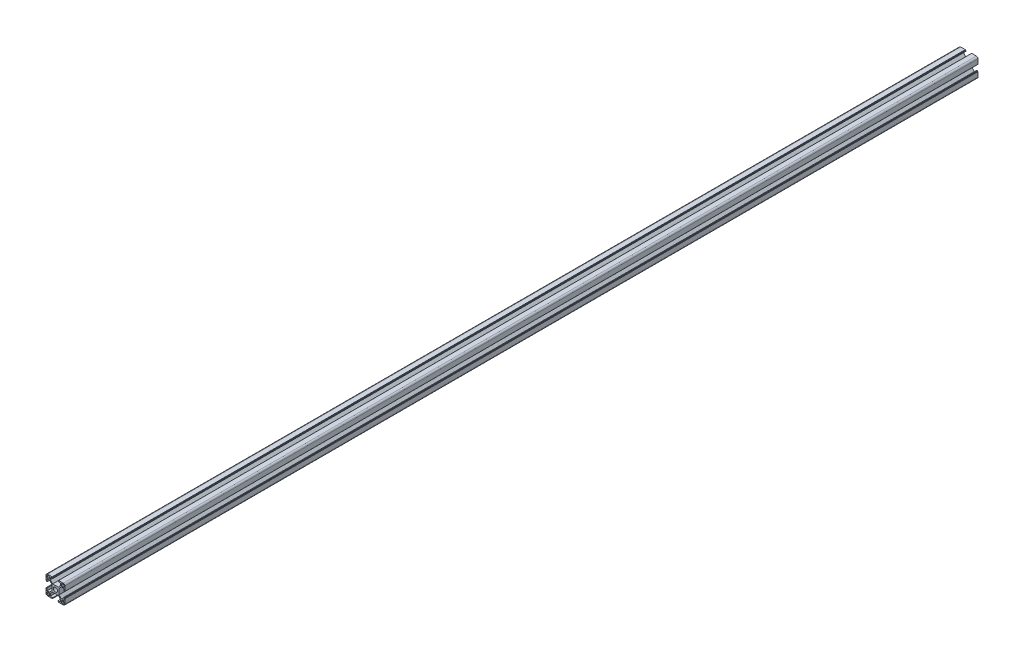
SolidWorks part; units mm, degrees
material "6061-T6 (SS)"
ref_plane "前视基准面" through (0, 0, 0) normal (0, 0, 1) x (1, 0, 0)
ref_plane "上视基准面" through (0, 0, 0) normal (0, 1, 0) x (1, 0, 0)
ref_plane "右视基准面" through (0, 0, 0) normal (1, 0, 0) x (0, 0, -1)
sketch "Sketch1" plane through (0, 0, 0) normal (0, 0, 1) x (1, 0, 0)
  line L0 (-5.1, 15) -> (-5.1, 14.2)
  line L1 (-12.5, -15) -> (12.5, -15)
  line L2 (-15, -12.5) -> (-15, 12.5)
  line L3 (-12.5, 15) -> (12.5, 15)
  line L4 (15, -12.5) -> (15, 12.5)
  line L5 (-15, -15) -> (15, 15) construction
  line L6 (-15, 15) -> (15, -15) construction
  line L7 (-5.1, 14.2) -> (-4.1, 14.2)
  line L8 (-4.1, 14.2) -> (-4.1, 13.2)
  line L9 (-4.1, 13.2) -> (-8.25, 13.2)
  line L10 (-8.25, 13.2) -> (-8.25, 9.5228)
  line L11 (-8.25, 9.5228) -> (-4.4272, 5.7)
  line L12 (-4.4272, 5.7) -> (4.4272, 5.7)
  line L13 (-5.1, 15) -> (5.1, 15)
  line L14 (0, 15) -> (0, 5.7) construction
  line L15 (8.25, 9.5228) -> (4.4272, 5.7)
  line L16 (8.25, 13.2) -> (8.25, 9.5228)
  line L17 (4.1, 13.2) -> (8.25, 13.2)
  line L18 (4.1, 14.2) -> (4.1, 13.2)
  line L19 (5.1, 14.2) -> (4.1, 14.2)
  line L20 (5.1, 15) -> (5.1, 14.2)
  line L21 (15, 5.1) -> (14.2, 5.1)
  line L22 (14.2, 5.1) -> (14.2, 4.1)
  line L23 (14.2, 4.1) -> (13.2, 4.1)
  line L24 (13.2, 4.1) -> (13.2, 8.25)
  line L25 (13.2, 8.25) -> (9.5228, 8.25)
  line L26 (9.5228, 8.25) -> (5.7, 4.4272)
  line L27 (5.7, 4.4272) -> (5.7, -4.4272)
  line L28 (15, 5.1) -> (15, -5.1)
  line L29 (9.5228, -8.25) -> (5.7, -4.4272)
  line L30 (13.2, -8.25) -> (9.5228, -8.25)
  line L31 (13.2, -4.1) -> (13.2, -8.25)
  line L32 (14.2, -4.1) -> (13.2, -4.1)
  line L33 (14.2, -5.1) -> (14.2, -4.1)
  line L34 (15, -5.1) -> (14.2, -5.1)
  line L35 (15, 0) -> (5.7, 0) construction
  line L36 (5.1, -15) -> (5.1, -14.2)
  line L37 (5.1, -14.2) -> (4.1, -14.2)
  line L38 (4.1, -14.2) -> (4.1, -13.2)
  line L39 (4.1, -13.2) -> (8.25, -13.2)
  line L40 (8.25, -13.2) -> (8.25, -9.5228)
  line L41 (8.25, -9.5228) -> (4.4272, -5.7)
  line L42 (4.4272, -5.7) -> (-4.4272, -5.7)
  line L43 (5.1, -15) -> (-5.1, -15)
  line L44 (-8.25, -9.5228) -> (-4.4272, -5.7)
  line L45 (-8.25, -13.2) -> (-8.25, -9.5228)
  line L46 (-4.1, -13.2) -> (-8.25, -13.2)
  line L47 (-4.1, -14.2) -> (-4.1, -13.2)
  line L48 (-5.1, -14.2) -> (-4.1, -14.2)
  line L49 (-5.1, -15) -> (-5.1, -14.2)
  line L50 (0, -15) -> (0, -5.7) construction
  line L51 (-15, -5.1) -> (-14.2, -5.1)
  line L52 (-14.2, -5.1) -> (-14.2, -4.1)
  line L53 (-14.2, -4.1) -> (-13.2, -4.1)
  line L54 (-13.2, -4.1) -> (-13.2, -8.25)
  line L55 (-13.2, -8.25) -> (-9.5228, -8.25)
  line L56 (-9.5228, -8.25) -> (-5.7, -4.4272)
  line L57 (-5.7, -4.4272) -> (-5.7, 4.4272)
  line L58 (-15, -5.1) -> (-15, 5.1)
  line L59 (-9.5228, 8.25) -> (-5.7, 4.4272)
  line L60 (-13.2, 8.25) -> (-9.5228, 8.25)
  line L61 (-13.2, 4.1) -> (-13.2, 8.25)
  line L62 (-14.2, 4.1) -> (-13.2, 4.1)
  line L63 (-14.2, 5.1) -> (-14.2, 4.1)
  line L64 (-15, 5.1) -> (-14.2, 5.1)
  line L65 (-15, 0) -> (-5.7, 0) construction
  line L66 (0, 0) -> (0, 5.7) construction
  circle A0 centre (0, 0) radius 3.4
  arc A1 (-12.5, -15) -> (-15, -12.5) centre (-12.5, -12.5) cw
  arc A2 (12.5, -15) -> (15, -12.5) centre (12.5, -12.5) ccw
  arc A3 (12.5, 15) -> (15, 12.5) centre (12.5, 12.5) cw
  arc A4 (-15, 12.5) -> (-12.5, 15) centre (-12.5, 12.5) cw
  point P0 (0, 0)
  dimension "D3" = 6.8
  dimension "D12" = 2.5
  dimension "D1" = 30
  dimension "D2" = 30
  dimension "D4" = 16.5
  dimension "D5" = 8.2
  dimension "D6" = 10.2
  dimension "D7" = 7.5
  dimension "D9" = 1.8
  dimension "D10" = 1.8
  dimension "D11" = 0.8
  dimension "D8" = 4
extrude "Extrude1" add sketch "Sketch1" along normal blind 1450 contours A4 L2 L64 L63 L62 L61 L60 L59 L57 L56 L55 L54 L53 L52 L51 A1 L1 L49 L48 L47 L46 L45 L44 L42 L41 L40 L39 L38 L37 L36 A2 L4 L34 L33 L32 L31 L30 L29 L27 L26 L25 L24 L23 L22 L21 A3 L3 L20
sketch "Sketch2" plane through (0, 0, 1450) normal (0, 0, 1) x (1, 0, 0)
  line L0 (13.7, 12.7) -> (13.7, 10.55)
  line L1 (-12.7, 13.7) -> (-10.55, 13.7)
  line L2 (-13.7, 12.7) -> (-13.7, 10.55)
  line L3 (-12.7, 9.55) -> (-10.55, 9.55)
  line L4 (-9.55, 12.7) -> (-9.55, 10.55)
  line L5 (-13.7, 13.7) -> (-9.55, 9.55) construction
  line L6 (-13.7, 9.55) -> (-9.55, 13.7) construction
  line L7 (12.7, 13.7) -> (10.55, 13.7)
  line L8 (9.55, 12.7) -> (9.55, 10.55)
  line L9 (12.7, 9.55) -> (10.55, 9.55)
  line L10 (12.7, -13.7) -> (10.55, -13.7)
  line L11 (13.7, -12.7) -> (13.7, -10.55)
  line L12 (12.7, -9.55) -> (10.55, -9.55)
  line L13 (9.55, -12.7) -> (9.55, -10.55)
  line L14 (-13.7, -12.7) -> (-13.7, -10.55)
  line L15 (-12.7, -13.7) -> (-10.55, -13.7)
  line L16 (-9.55, -12.7) -> (-9.55, -10.55)
  line L17 (-12.7, -9.55) -> (-10.55, -9.55)
  line L18 (0, 0) -> (-9.55, 9.55) construction
  line L19 (-12.5, 15) -> (-5.1, 15) construction
  line L20 (-15, 5.1) -> (-15, 12.5) construction
  line L21 (-13.2, 8.25) -> (-9.5228, 8.25) construction
  line L22 (-8.25, 13.2) -> (-8.25, 9.5228) construction
  arc A0 (-13.7, -12.7) -> (-12.7, -13.7) centre (-12.7, -12.7) ccw
  arc A1 (-10.55, -13.7) -> (-9.55, -12.7) centre (-10.55, -12.7) ccw
  arc A2 (-9.55, -10.55) -> (-10.55, -9.55) centre (-10.55, -10.55) ccw
  arc A3 (-13.7, -10.55) -> (-12.7, -9.55) centre (-12.7, -10.55) cw
  arc A4 (13.7, -10.55) -> (12.7, -9.55) centre (12.7, -10.55) ccw
  arc A5 (12.7, -13.7) -> (13.7, -12.7) centre (12.7, -12.7) ccw
  arc A6 (10.55, -13.7) -> (9.55, -12.7) centre (10.55, -12.7) cw
  arc A7 (10.55, -9.55) -> (9.55, -10.55) centre (10.55, -10.55) ccw
  arc A8 (13.7, 12.7) -> (12.7, 13.7) centre (12.7, 12.7) ccw
  arc A9 (13.7, 10.55) -> (12.7, 9.55) centre (12.7, 10.55) cw
  arc A10 (9.55, 10.55) -> (10.55, 9.55) centre (10.55, 10.55) ccw
  arc A11 (10.55, 13.7) -> (9.55, 12.7) centre (10.55, 12.7) ccw
  arc A12 (-10.55, 13.7) -> (-9.55, 12.7) centre (-10.55, 12.7) cw
  arc A13 (-10.55, 9.55) -> (-9.55, 10.55) centre (-10.55, 10.55) ccw
  arc A14 (-13.7, 10.55) -> (-12.7, 9.55) centre (-12.7, 10.55) ccw
  arc A15 (-12.7, 13.7) -> (-13.7, 12.7) centre (-12.7, 12.7) ccw
  point P0 (-11.625, 11.625)
  dimension "D2" = 1
  dimension "D3" = 1.3
  dimension "D4" = 1.3
  dimension "D5" = 1.3
  dimension "D6" = 1.3
  dimension "D1" = 4
extrude "Extrude2" cut sketch "Sketch2" against normal through all
